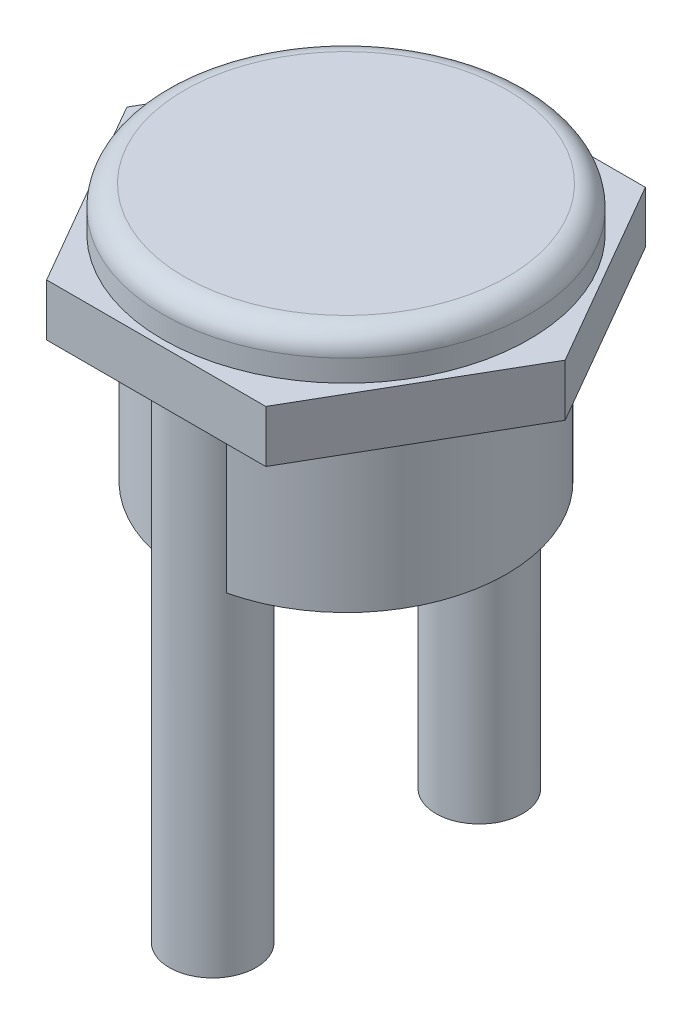
SolidWorks part; units mm, degrees
ref_plane "Front Plane" through (0, 0, 0) normal (0, 0, 1) x (1, 0, 0)
ref_plane "Top Plane" through (0, 0, 0) normal (0, 1, 0) x (1, 0, 0)
ref_plane "Right Plane" through (0, 0, 0) normal (1, 0, 0) x (0, 0, -1)
sketch "Sketch1" plane through (0, 0, 0) normal (0, 1, 0) x (1, 0, 0)
  circle A0 centre (0, 0) radius 10.7315
  dimension "D1" = 21.463
extrude "Boss-Extrude1" add sketch "Sketch1" along normal blind 2.54
sketch "Sketch2" plane through (0, 0, 0) normal (0, -1, 0) x (1, 0, 0)
  line L1 (-12.8316, 0) -> (-6.4158, -11.1125)
  line L2 (-6.4158, -11.1125) -> (6.4158, -11.1125)
  line L3 (6.4158, -11.1125) -> (12.8316, 0)
  line L4 (12.8316, 0) -> (6.4158, 11.1125)
  line L5 (6.4158, 11.1125) -> (-6.4158, 11.1125)
  line L6 (-6.4158, 11.1125) -> (-12.8316, 0)
  circle A0 centre (0, 0) radius 11.1125 construction
  circle A1 centre (0, 0) radius 10.7315 construction
  dimension "D1" = 22.225
extrude "Boss-Extrude2" add sketch "Sketch2" along normal blind 3.048
sketch "Sketch4" plane through (0, -3.048, 0) normal (0, -1, 0) x (1, 0, 0)
  circle A0 centre (0, 0) radius 9.398
  dimension "D1" = 18.796
extrude "Boss-Extrude4" add sketch "Sketch4" along normal blind 9.525
sketch "Sketch3" plane through (0, -3.048, 0) normal (0, -1, 0) x (1, 0, 0)
  line L0 (0, 7.8066) -> (0, -7.8066) construction
  circle A0 centre (0, 7.8066) radius 2.54
  circle A1 centre (0, -7.8066) radius 2.54
  point P4 (0, 0)
  dimension "D1" = 5.08
extrude "Boss-Extrude3" add sketch "Sketch3" along normal blind 29
fillet "Fillet1" radius 1.27 1 edges at (0, 2.54, 10.7315)
equation "\"..12in\"=0.0625"
